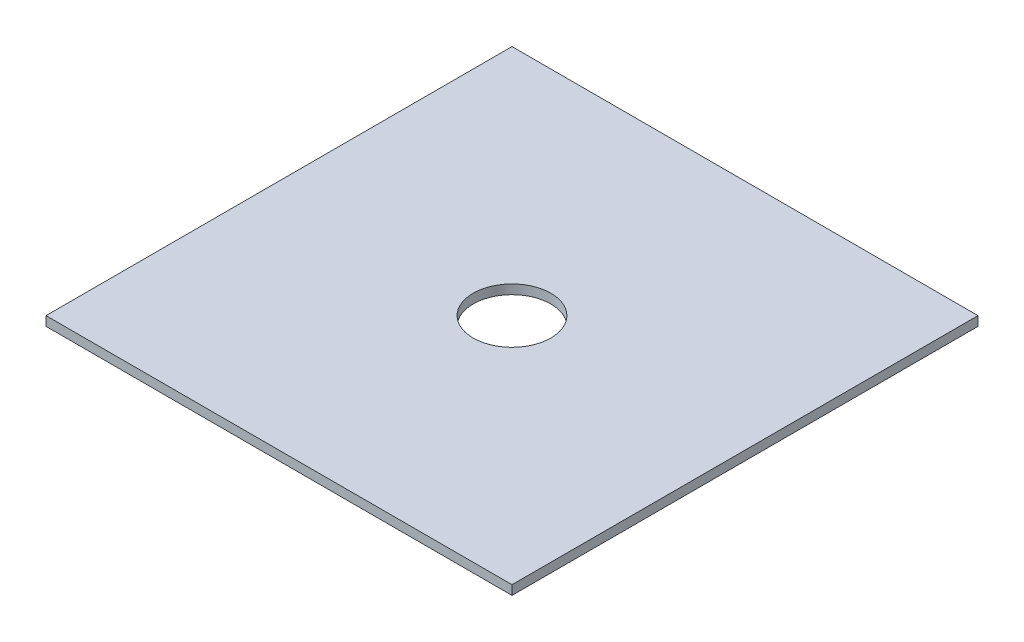
SolidWorks part; units mm, degrees
ref_plane "Front Plane" through (0, 0, 0) normal (0, 0, 1) x (1, 0, 0)
ref_plane "Top Plane" through (0, 0, 0) normal (0, 1, 0) x (1, 0, 0)
ref_plane "Right Plane" through (0, 0, 0) normal (1, 0, 0) x (0, 0, -1)
sketch "Sketch1" plane through (0, 0, 0) normal (0, 1, 0) x (1, 0, 0)
  line L1 (-75, -75) -> (75, -75)
  line L2 (-75, -75) -> (-75, 75)
  line L3 (-75, 75) -> (75, 75)
  line L4 (75, -75) -> (75, 75)
  line L5 (0, 75) -> (0, -75) construction
  line L6 (-75, 0) -> (75, 0) construction
  point P0 (0, 0)
  dimension "D1" = 150
  dimension "D2" = 150
extrude "Boss-Extrude1" add sketch "Sketch1" along normal blind 3
sketch "Sketch2" plane through (0, 3, 0) normal (0, 1, 0) x (1, 0, 0)
  circle A0 centre (0, 0) radius 12.5
  dimension "D1" = 25
extrude "Cut-Extrude1" cut sketch "Sketch2" against normal blind 3
